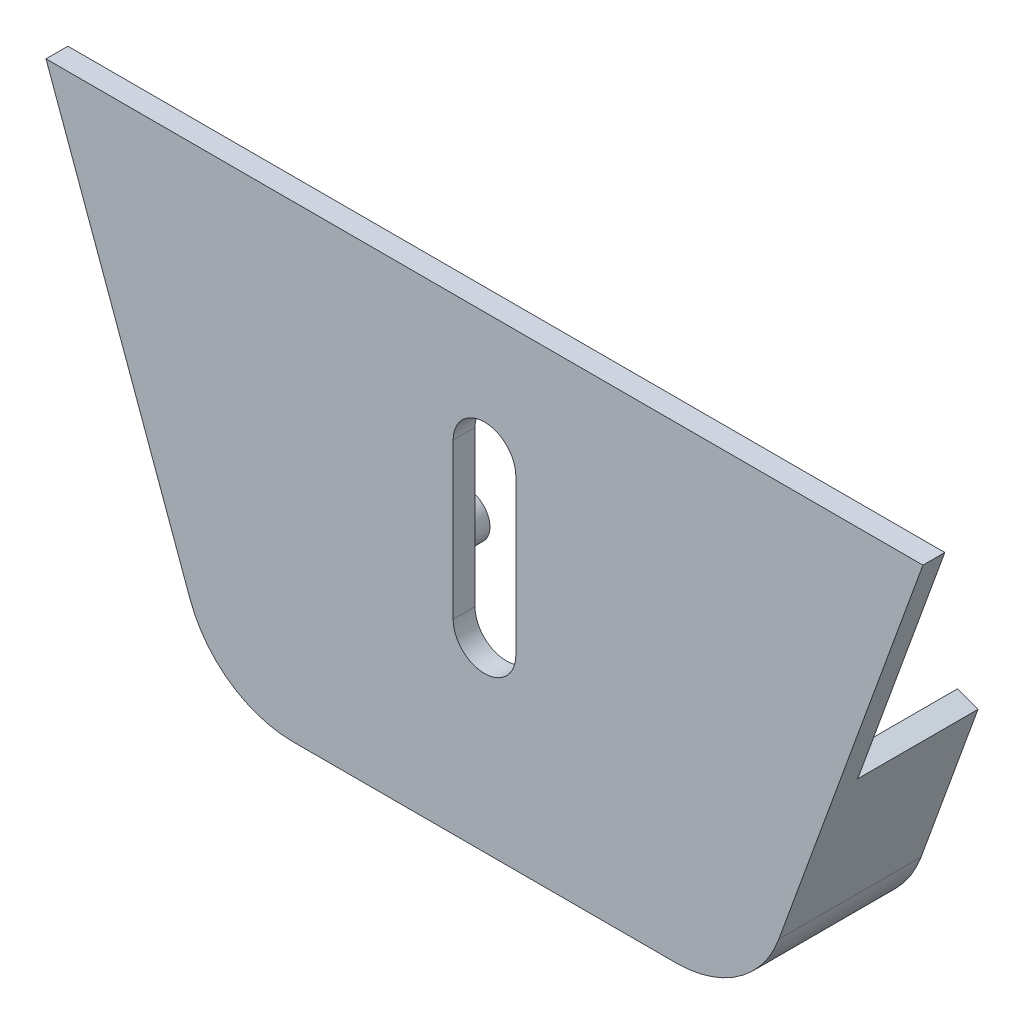
SolidWorks part; units mm, degrees
ref_plane "Front Plane" through (0, 0, 0) normal (0, 0, 1) x (1, 0, 0)
ref_plane "Top Plane" through (0, 0, 0) normal (0, 1, 0) x (1, 0, 0)
ref_plane "Right Plane" through (0, 0, 0) normal (1, 0, 0) x (0, 0, -1)
sketch "Sketch1" plane through (0, 0, 0) normal (0, 0, 1) x (1, 0, 0)
  line L0 (-17.5, 0) -> (17.5, 0) construction
  line L1 (-17.5, -10) -> (17.5, -10)
  line L2 (-26.8969, -3.4202) -> (-40.0654, 32.76)
  line L3 (-40.0654, 32.76) -> (40.0654, 32.76)
  line L4 (40.0654, 32.76) -> (26.8969, -3.4202)
  line L5 (40.0654, 32.76) -> (-40.0654, 32.76) construction
  line L6 (26.8969, -3.4202) -> (40.0654, 32.76) construction
  line L7 (-40.0654, 32.76) -> (-30.3893, 6.1749) construction
  line L8 (0, 21.1909) -> (0, 7.0144) construction
  line L9 (2.8635, 21.1909) -> (2.8635, 7.0144)
  line L10 (-2.8635, 21.1909) -> (-2.8635, 7.0144)
  arc A0 (-26.8969, -3.4202) -> (-17.5, -10) centre (-17.5, 0) ccw
  arc A1 (17.5, -10) -> (26.8969, -3.4202) centre (17.5, 0) ccw
  circle A2 centre (17.5, 0) radius 2 construction
  circle A3 centre (17.5, 0) radius 2
  circle A4 centre (-17.5, 0) radius 2 construction
  circle A5 centre (-17.5, 0) radius 2
  arc A6 (2.8635, 21.1909) -> (-2.8635, 21.1909) centre (0, 21.1909) ccw
  arc A9 (-2.8635, 7.0144) -> (2.8635, 7.0144) centre (0, 7.0144) ccw
  point P13 (0, 14.1027)
  dimension "D3" = 20
  dimension "D4" = 20
  dimension "D1" = 35
  dimension "D2" = 17.5
extrude "Boss-Extrude1" add sketch "Sketch1" along normal blind 2
sketch "Sketch2" plane through (0, 0, 2) normal (0, 0, 1) x (1, 0, 0)
  circle A0 centre (-17.5, 0) radius 2 construction
  circle A1 centre (-17.5, 0) radius 2
  circle A2 centre (-17.5, 0) radius 3.5
  circle A3 centre (17.5, 0) radius 2 construction
  circle A4 centre (17.5, 0) radius 2
  circle A5 centre (17.5, 0) radius 3.5
  dimension "D1" = 1.5
  dimension "D2" = 1.5
extrude "Boss-Extrude2" add sketch "Sketch2" against normal blind 4 from vertex at -2 starting at point (-17.5, -10, 0)
sketch "Sketch4" plane through (0, 0, 0) normal (0, 0, -1) x (-1, 0, 0)
  line L0 (-39.1029, 10.8636) -> (39.5724, 10.8636) construction
  line L1 (-26.8969, -3.4202) -> (-40.0654, 32.76) construction
  line L2 (-26.8969, -3.4202) -> (-32.0958, 10.8636)
  line L3 (40.0654, 32.76) -> (26.8969, -3.4202) construction
  line L4 (32.0958, 10.8636) -> (26.8969, -3.4202)
  line L5 (-25.0175, -2.7362) -> (-30.2164, 11.5477)
  line L6 (30.2164, 11.5477) -> (25.0175, -2.7362)
  line L7 (-32.0958, 10.8636) -> (-30.2164, 11.5477)
  line L8 (30.2164, 11.5477) -> (32.0958, 10.8636)
  line L9 (17.5, -8) -> (17.5, -10)
  line L10 (-17.5, -10) -> (-17.5, -8)
  arc A0 (-26.8969, -3.4202) -> (-17.5, -10) centre (-17.5, 0) ccw construction
  arc A1 (-26.8969, -3.4202) -> (-17.5, -10) centre (-17.5, 0) ccw
  arc A2 (17.5, -10) -> (26.8969, -3.4202) centre (17.5, 0) ccw construction
  arc A3 (17.5, -10) -> (26.8969, -3.4202) centre (17.5, 0) ccw
  arc A4 (-25.0175, -2.7362) -> (-17.5, -8) centre (-17.5, 0) ccw
  arc A5 (17.5, -8) -> (25.0175, -2.7362) centre (17.5, 0) ccw
  dimension "D1" = 2
  dimension "D2" = 2
extrude "Boss-Extrude3" add sketch "Sketch4" along normal blind 11
sketch "Sketch5" plane through (0, 0, 2) normal (0, 0, 1) x (1, 0, 0)
  circle A0 centre (-17.5, 0) radius 2 construction
  circle A1 centre (-17.5, 0) radius 2
  circle A2 centre (17.5, 0) radius 2 construction
  circle A3 centre (17.5, 0) radius 2
extrude "Boss-Extrude4" add sketch "Sketch5" against normal blind 16
